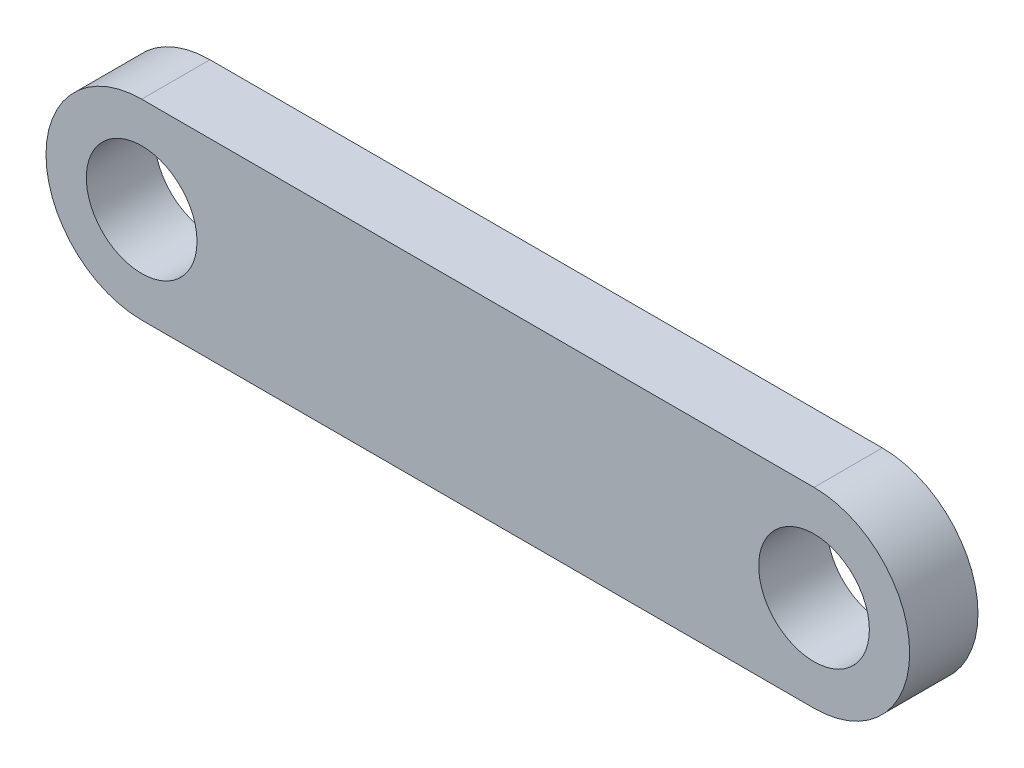
SolidWorks part; units mm, degrees
material "Hexcel AS4C (3000 丝)"
ref_plane "前视基准面" through (0, 0, 0) normal (0, 0, 1) x (1, 0, 0)
ref_plane "上视基准面" through (0, 0, 0) normal (0, 1, 0) x (1, 0, 0)
ref_plane "右视基准面" through (0, 0, 0) normal (1, 0, 0) x (0, 0, -1)
sketch "草图1" plane through (0, 0, 0) normal (0, 0, 1) x (1, 0, 0)
  line L0 (0, -7) -> (49.2, -7)
  line L1 (49.2, 7) -> (0, 7)
  circle A0 centre (0, 0) radius 4.05
  circle A1 centre (49.2, 0) radius 4.05
  circle A2 centre (0, 0) radius 7
  circle A3 centre (49.2, 0) radius 7
  dimension "D1" = 8.1
  dimension "D2" = 14
  dimension "D3" = 49.2
extrude "凸台-拉伸1" add sketch "草图1" along normal blind 5 contours A3 L1 A2 L0 | A2 A0 | A3 A1
